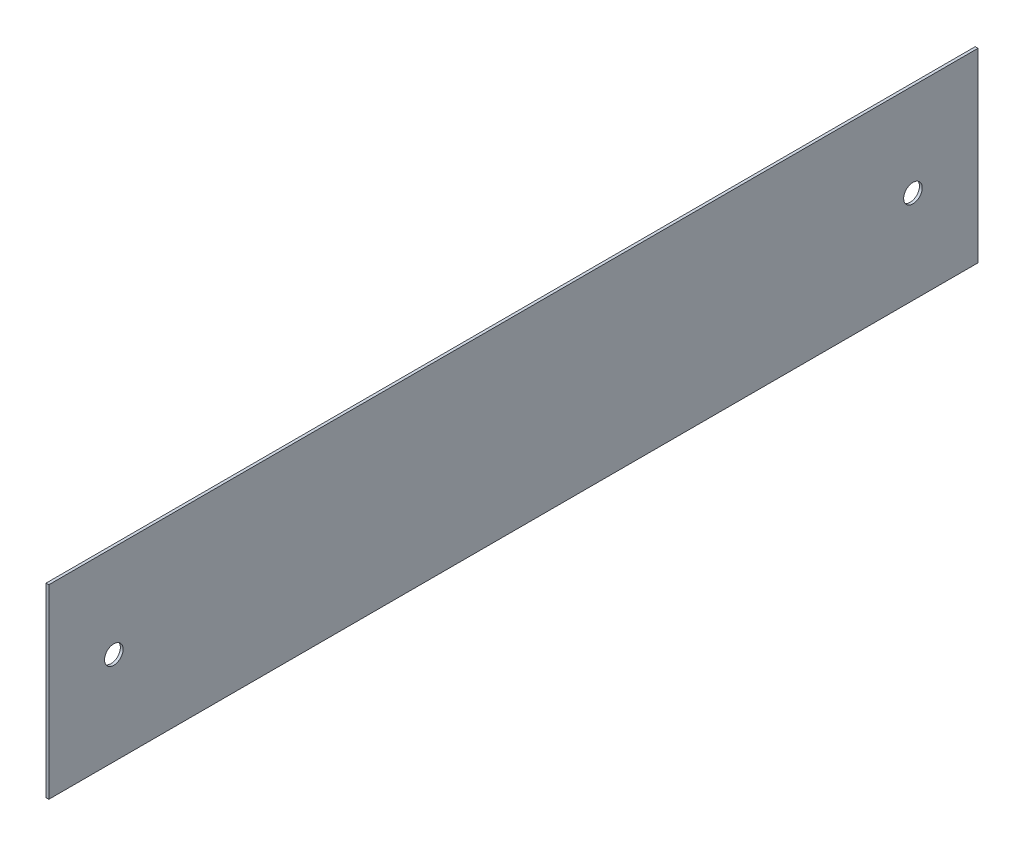
SolidWorks part; units mm, degrees
ref_plane "Front Plane" through (0, 0, 0) normal (0, 0, 1) x (1, 0, 0)
ref_plane "Top Plane" through (0, 0, 0) normal (0, 1, 0) x (1, 0, 0)
ref_plane "Right Plane" through (0, 0, 0) normal (1, 0, 0) x (0, 0, -1)
sketch "Sketch1" plane through (0, 0, 0) normal (1, 0, 0) x (0, 0, -1)
  line L0 (-500, 0) -> (500, 0)
  point P4 (0, 0)
  dimension "D1" = 1000
extrude "Extrude-Thin1" add sketch "Sketch1" along normal blind 3 thin
sketch "Sketch3" plane through (3, 0, 0) normal (1, 0, 0) x (0, 0, -1)
  line L0 (-500, -100) -> (500, -100) construction
  line L1 (-500, -200) -> (-500, 0) construction
  line L2 (500, 0) -> (500, -200) construction
  circle A0 centre (-430, -100) radius 10
  circle A1 centre (430, -100) radius 10
  dimension "D1" = 20
  dimension "D3" = 20
  dimension "D2" = 70
  dimension "D4" = 70
extrude "Cut-Extrude2" cut sketch "Sketch3" against normal blind 5
